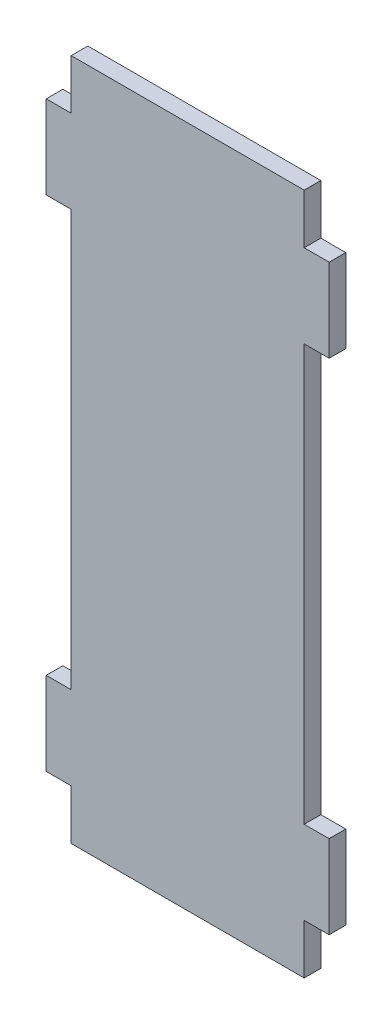
SolidWorks part; units mm, degrees
ref_plane "Alzado" through (0, 0, 0) normal (0, 0, 1) x (1, 0, 0)
ref_plane "Planta" through (0, 0, 0) normal (0, 1, 0) x (1, 0, 0)
ref_plane "Vista lateral" through (0, 0, 0) normal (1, 0, 0) x (0, 0, -1)
sketch "Croquis1" plane through (0, 0, 0) normal (0, 0, 1) x (1, 0, 0)
  line L4 (0, 0) -> (0, -6)
  line L5 (0, -6) -> (-3, -6)
  line L6 (-3, -6) -> (-3, -16)
  line L7 (-3, -16) -> (0, -16)
  line L8 (0, -16) -> (0, -66)
  line L9 (0, -66) -> (-3, -66)
  line L10 (-3, -66) -> (-3, -76)
  line L11 (-3, -76) -> (0, -76)
  line L12 (0, -76) -> (0, -82)
  line L13 (0, -82) -> (28, -82)
  line L14 (31, -76) -> (31, -66)
  line L15 (28, 0) -> (0, 0)
  line L16 (31, -6) -> (28, -6)
  line L17 (28, -6) -> (28, 0)
  line L18 (31, -16) -> (28, -16)
  line L19 (28, -16) -> (28, -66)
  line L20 (28, -66) -> (31, -66)
  line L21 (31, -16) -> (31, -6)
  line L22 (31, -76) -> (28, -76)
  line L23 (28, -76) -> (28, -82)
  dimension "D1" = 82
  dimension "D2" = 3
  dimension "D3" = 6
  dimension "D4" = 50
  dimension "D5" = 10
  dimension "D6" = 10
  dimension "D7" = 3
  dimension "D8" = 3
  dimension "D9" = 28
  dimension "D10" = 10
  dimension "D11" = 28
  dimension "D12" = 3
extrude "Saliente-Extruir1" add sketch "Croquis1" against normal blind 2
